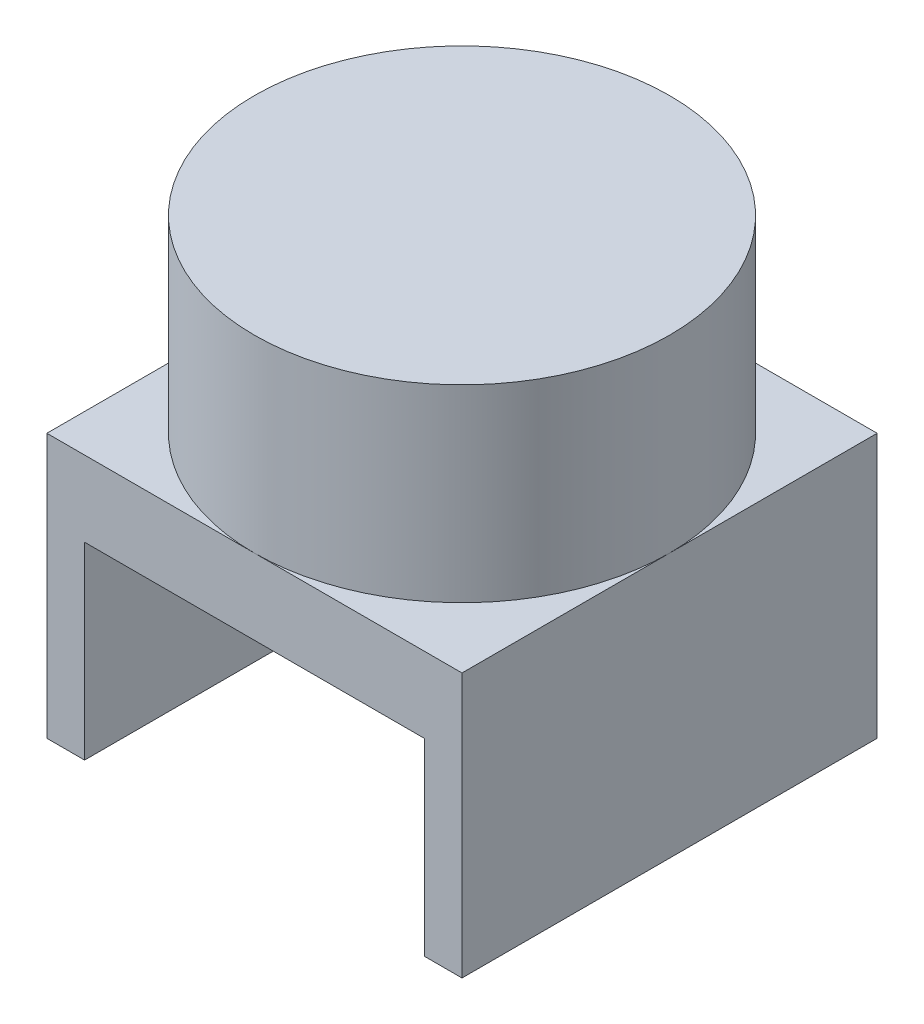
SolidWorks part; units mm, degrees
ref_plane "Front View" through (0, 0, 0) normal (0, 0, 1) x (1, 0, 0)
ref_plane "Upper View" through (0, 0, 0) normal (0, 1, 0) x (1, 0, 0)
ref_plane "Right View" through (0, 0, 0) normal (1, 0, 0) x (0, 0, -1)
sketch "Sketch1" plane through (0, 0, 0) normal (0, 1, 0) x (1, 0, 0)
  circle A0 centre (0, 0) radius 5.5
extrude "Boss-Extrude1" add sketch "Sketch1" along normal blind 5
sketch "Sketch2" plane through (0, 0, 0) normal (0, -1, 0) x (-1, 0, 0)
  line L0 (5.5, 5.5) -> (-5.5, 5.5)
  line L2 (-5.5, 5.5) -> (-5.5, -5.5)
  line L3 (-5.5, -5.5) -> (5.5, -5.5)
  line L4 (5.5, -5.5) -> (5.5, 5.5)
extrude "Boss-Extrude2" add sketch "Sketch2" along normal blind 2
sketch "Sketch3" plane through (0, -2, 0) normal (0, -1, 0) x (-1, 0, 0)
  line L0 (5.5, -5.5) -> (4.5, -5.5)
  line L1 (4.5, -5.5) -> (4.5, 5.5)
  line L2 (5.5, 5.5) -> (-5.5, 5.5) construction
  line L3 (4.5, 5.5) -> (5.5, 5.5)
  line L4 (5.5, 5.5) -> (5.5, -5.5)
  line L5 (-5.5, -5.5) -> (-4.5, -5.5)
  line L6 (-5.5, -5.5) -> (5.5, -5.5) construction
  line L7 (-4.5, -5.5) -> (-4.5, 5.5)
  line L8 (-4.5, 5.5) -> (-5.5, 5.5)
  line L9 (-5.5, 5.5) -> (-5.5, -5.5)
extrude "Boss-Extrude3" add sketch "Sketch3" along normal blind 5
